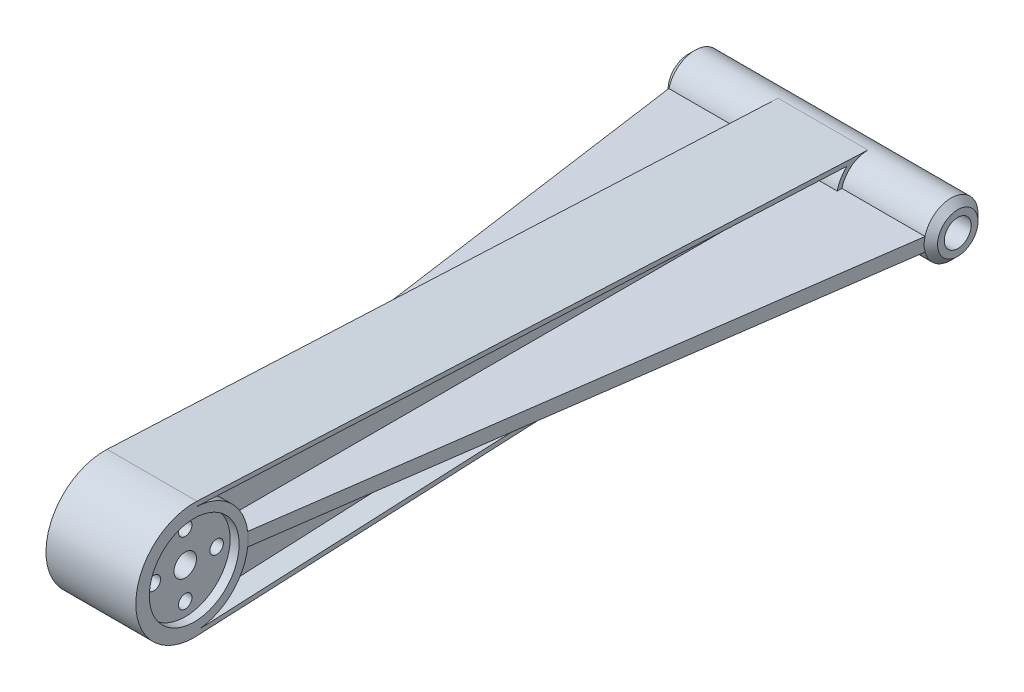
SolidWorks part; units mm, degrees
ref_plane "前视基准面" through (0, 0, 0) normal (0, 0, 1) x (1, 0, 0)
ref_plane "上视基准面" through (0, 0, 0) normal (0, 1, 0) x (1, 0, 0)
ref_plane "右视基准面" through (0, 0, 0) normal (1, 0, 0) x (0, 0, -1)
sketch "草图1" plane through (0, 0, 0) normal (1, 0, 0) x (0, 0, -1)
  line L0 (-39.662, 0) -> (211.1332, 0) construction
  line L1 (0.6072, 12.9858) -> (150, 6)
  line L2 (0, -13) -> (150, -6)
  circle A0 centre (0, 0) radius 13
  circle A1 centre (150, 0) radius 6
  dimension "D1" = 150
  dimension "D2" = 26
  dimension "D3" = 12
extrude "凸台-拉伸1" add sketch "草图1" along normal mid plane 20 contours L0 A0 L2 | A0 L0 | A0 L0 A1 L1 | L0 A0 L2 A1 | L0 A1 | A1 L0
sketch "草图2" plane through (-10, 0, 0) normal (-1, 0, 0) x (0, 0, 1)
  circle A0 centre (0, 0) radius 10
  dimension "D1" = 20
extrude "切除-拉伸1" cut sketch "草图2" against normal blind 2
sketch "草图4" plane through (10, 0, 0) normal (1, 0, 0) x (0, 0, -1)
  circle A0 centre (0, 0) radius 10
  dimension "D1" = 20
extrude "切除-拉伸2" cut sketch "草图4" against normal blind 2
sketch "草图5" plane through (8, 0, 0) normal (1, 0, 0) x (0, 0, -1)
  circle A0 centre (0, 0) radius 7 construction
  circle A1 centre (7, 0) radius 1.5
  circle A2 centre (0, 7) radius 1.5
  circle A3 centre (-7, 0) radius 1.5
  circle A4 centre (0, -7) radius 1.5
  circle A5 centre (0, 0) radius 2.5
  dimension "D1" = 14
  dimension "D2" = 3
  dimension "D3" = 3
  dimension "D4" = 3
  dimension "D5" = 3
  dimension "D6" = 5
extrude "切除-拉伸3" cut sketch "草图5" against normal through all
sketch "草图7" plane through (0, 0, 0) normal (1, 0, 0) x (0, 0, -1)
  circle A0 centre (150, 0) radius 6
  dimension "D1" = 12
extrude "凸台-拉伸3" add sketch "草图7" along normal mid plane 60
sketch "草图8" plane through (30, 0, 0) normal (1, 0, 0) x (0, 0, -1)
  circle A0 centre (150, 0) radius 3
  dimension "D1" = 6
extrude "切除-拉伸4" cut sketch "草图8" against normal through all
chamfer "倒角1" distance 1.5 angle 45 2 edges at (-30, 0, -156) (30, 0, -156)
sketch "草图9" plane through (-10, 0, 0) normal (-1, 0, 0) x (0, 0, 1)
  line L13 (0.0466, -12.0011) -> (-145.3325, -5.2167)
  line L14 (-145.3329, 5.2171) -> (-0.5605, 11.9869)
  line L15 (0.0466, -12.0011) -> (-145.3325, -5.2167)
  line L16 (-145.3329, 5.2171) -> (-0.5605, 11.9869)
  arc A10 (-0.5605, 11.9869) -> (0.0229, -12) centre (0, 0) ccw
  arc A11 (-145.3325, -5.2167) -> (-145.3329, 5.2171) centre (-150, 0) ccw
  arc A12 (-145.3325, -5.2167) -> (-145.3329, 5.2171) centre (-150, 0) ccw
  dimension "D1" = 1
extrude "切除-拉伸5" cut sketch "草图9" against normal blind 5 contours A12 L15 A10 L16
mirror "镜向1" about plane through (0, 0, 0) normal (1, 0, 0) of "切除-拉伸5"
sketch "草图10" plane through (0, 0, 0) normal (0, 1, 0) x (1, 0, 0)
  line L0 (-28.5, 144) -> (-10, 12)
rib "筋1" sketch "草图10" sketch "草图10" thickness 3 extrusion direction parallel to sketch draft on no parameters "D1"=3
mirror "镜向2" about plane through (0, 0, 0) normal (1, 0, 0) of "筋1"
